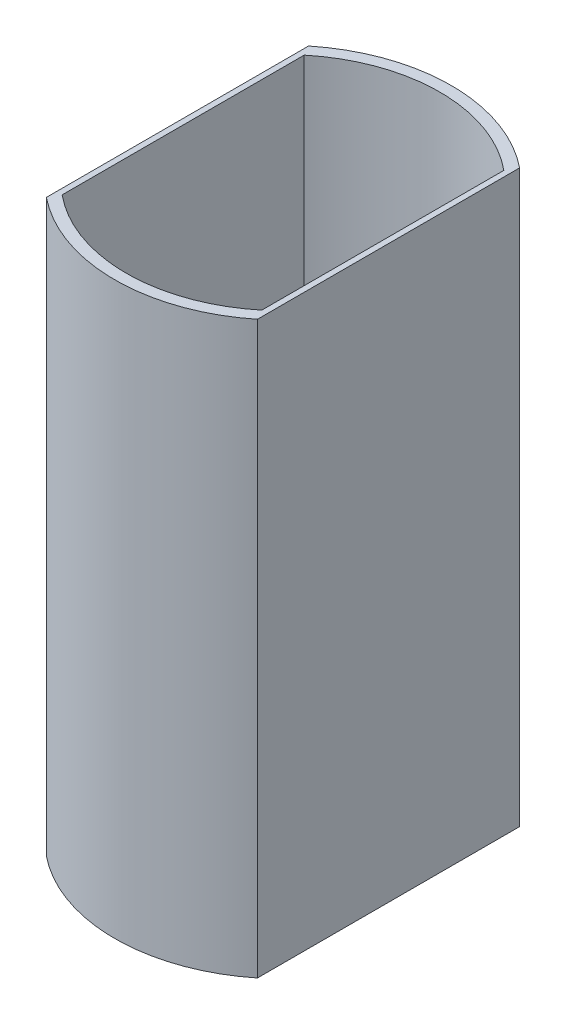
SolidWorks part; units mm, degrees
ref_plane "Спереди" through (0, 0, 0) normal (0, 0, 1) x (1, 0, 0)
ref_plane "Сверху" through (0, 0, 0) normal (0, 1, 0) x (1, 0, 0)
ref_plane "Справа" through (0, 0, 0) normal (1, 0, 0) x (0, 0, -1)
sketch "Эскиз1" plane through (0, 0, 0) normal (0, 1, 0) x (1, 0, 0)
  line L0 (0, 6.962) -> (0, -3.8315) construction
  line L1 (-1.75, 2.1213) -> (-1.75, -2.1213)
  line L2 (1.75, 2.1213) -> (1.75, -2.1213)
  line L3 (-1.85, 2.2978) -> (-1.85, -2.2978)
  line L4 (1.75, 6.962) -> (1.75, -3.8315) construction
  line L5 (-1.75, 6.962) -> (-1.75, -3.8315) construction
  line L6 (1.85, 2.2978) -> (1.85, -2.2978)
  line L8 (-1.85, 6.962) -> (-1.85, -3.8315) construction
  line L9 (1.85, 6.962) -> (1.85, -3.8315) construction
  arc A0 (1.75, 2.1213) -> (-1.75, 2.1213) centre (0, 0) ccw
  arc A1 (-1.75, -2.1213) -> (1.75, -2.1213) centre (0, 0) ccw
  arc A2 (-1.85, -2.2978) -> (1.85, -2.2978) centre (0, 0) ccw
  arc A3 (1.85, 2.2978) -> (-1.85, 2.2978) centre (0, 0) ccw
  dimension "D1" = 5.5
  dimension "D4" = 5.9
  dimension "D2" = 1.75
  dimension "D3" = 1.75
  dimension "D5" = 1.85
  dimension "D6" = 1.85
extrude "Бобышка-Вытянуть1" add sketch "Эскиз1" along normal blind 10
